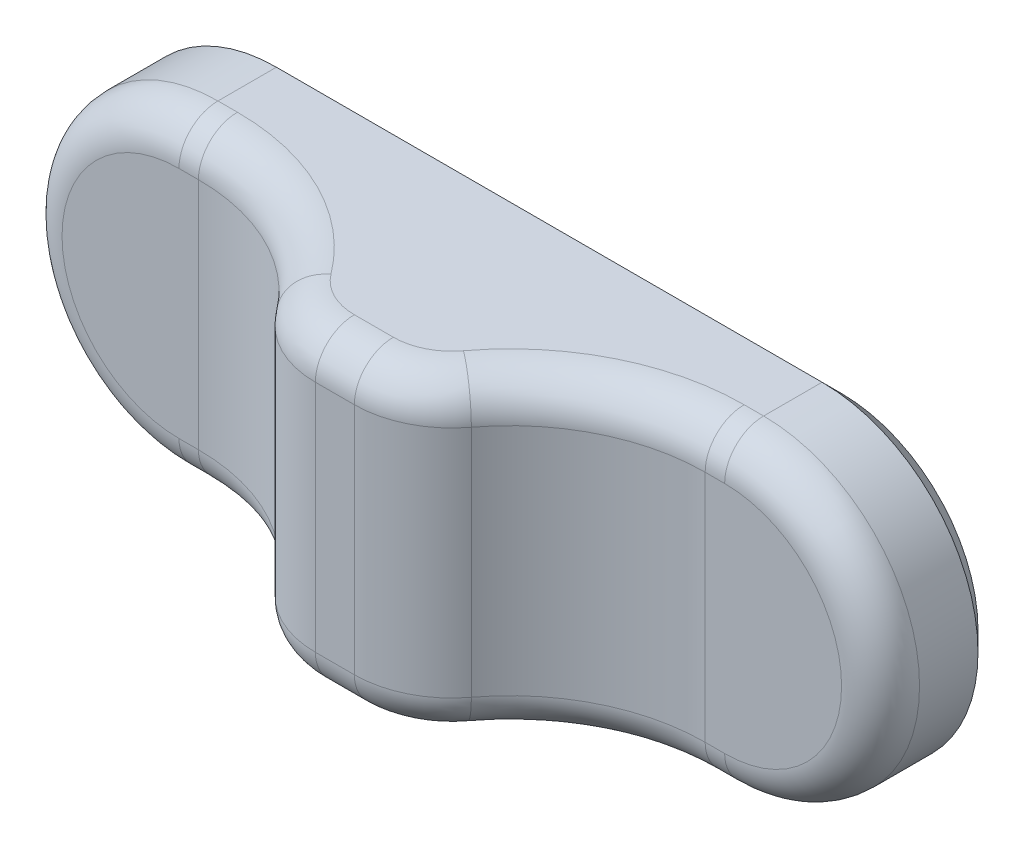
SolidWorks part; units mm, degrees
ref_plane "Front" through (0, 0, 0) normal (0, 0, 1) x (1, 0, 0)
ref_plane "Top" through (0, 0, 0) normal (0, 1, 0) x (1, 0, 0)
ref_plane "Right" through (0, 0, 0) normal (1, 0, 0) x (0, 0, -1)
sketch "Sketch1" plane through (0, 0, 0) normal (0, 0, 1) x (1, 0, 0)
  line L0 (5.475, -89.5) -> (-8.525, -89.5) construction
  line L1 (5.475, -93.5) -> (-8.525, -93.5)
  line L2 (5.475, -85.5) -> (-8.525, -85.5)
  line L3 (0, -87.975) -> (-3.05, -87.975) construction
  line L4 (0, -91.025) -> (0, -87.975) construction
  arc A0 (5.475, -93.5) -> (5.475, -85.5) centre (5.475, -89.5) ccw
  arc A1 (-8.525, -85.5) -> (-8.525, -93.5) centre (-8.525, -89.5) ccw
  point P2 (-1.525, -89.5)
  point P7 (0, 0)
  point P10 (-1.525, -87.975)
  point P11 (-1.525, -89.3859)
  point P14 (0, -89.5)
  dimension "D1" = 14
  dimension "D2" = 8
extrude "Boss-Extrude1" add sketch "Sketch1" along normal blind 6
sketch "Sketch2" plane through (0, -93.5, 0) normal (0, -1, 0) x (1, 0, 0)
  line L0 (4.4, 0) -> (-4.4, 0) construction
  line L1 (-12.525, 6) -> (-4.525, 6)
  line L2 (-12.525, 6) -> (-12.525, 3)
  line L3 (-12.525, 3) -> (-4.525, 3)
  line L4 (-4.525, 6) -> (-4.525, 3)
  line L5 (9.475, 6) -> (1.475, 6)
  line L6 (9.475, 6) -> (9.475, 3)
  line L7 (9.475, 3) -> (1.475, 3)
  line L8 (1.475, 6) -> (1.475, 3)
  dimension "D1" = 3
  dimension "D2" = 6
extrude "Cut-Extrude1" cut sketch "Sketch2" against normal through all
sketch "Sketch3" plane through (0, 0, 0) normal (0, 0, -1) x (-1, 0, 0)
  line L0 (-5.475, -85.5) -> (8.525, -85.5) construction
  line L1 (-0.075, -87.9) -> (3.125, -87.9)
  line L2 (-0.075, -87.9) -> (-0.075, -91.1)
  line L3 (-0.075, -91.1) -> (3.125, -91.1)
  line L4 (3.125, -87.9) -> (3.125, -91.1)
  line L5 (1.525, -85.5) -> (1.525, -87.9) construction
  line L6 (1.525, -91.1) -> (1.525, -93.5) construction
  line L7 (8.525, -93.5) -> (-5.475, -93.5) construction
  dimension "D1" = 3.2
  dimension "D2" = 3.2
extrude "Cut-Extrude2" cut sketch "Sketch3" against normal blind 5
fillet "Fillet1" radius 2.5 2 edges at (1.475, -89.5, 6) (-4.525, -89.5, 6)
fillet "Fillet2" radius 5 2 edges at (1.475, -89.5, 3) (-4.525, -89.5, 3)
fillet "Fillet3" radius 1 16 edges at (-8.275, -93.5, 3) (-5.7889, -93.5, 3.5279) (-3.143, -93.5, 5.7361) (-1.525, -93.5, 6) (0.093, -93.5, 5.7361) (2.7389, -93.5, 3.5279) (5.225, -93.5, 3) (9.475, -89.5, 3) (5.225, -85.5, 3) (2.7389, -85.5, 3.5279) (0.093, -85.5, 5.7361) (-1.525, -85.5, 6) (-3.143, -85.5, 5.7361) (-5.7889, -85.5, 3.5279) (-8.275, -85.5, 3) (-12.525, -89.5, 3)
chamfer "Chamfer1" distance 0.5 angle 45 4 edges at (-1.525, -85.5, 0) (-12.525, -89.5, 0) (9.475, -89.5, 0) (-1.525, -93.5, 0)
chamfer "Chamfer2" distance 1 angle 45 4 edges at (-1.525, -87.9, 5) (-3.125, -89.5, 5) (-1.525, -91.1, 5) (0.075, -89.5, 5)
